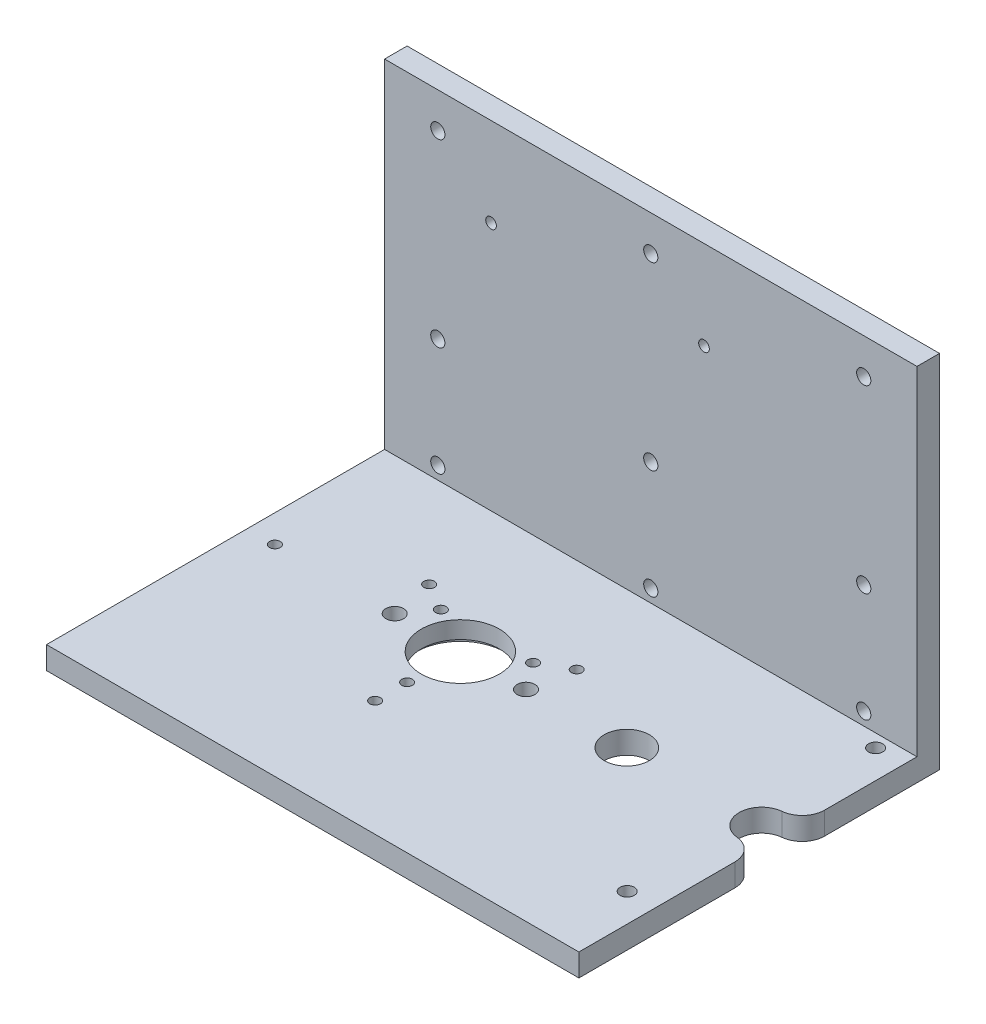
SolidWorks part; units mm, degrees
ref_plane "Alzado" through (0, 0, 0) normal (0, 0, 1) x (1, 0, 0)
ref_plane "Planta" through (0, 0, 0) normal (0, 1, 0) x (1, 0, 0)
ref_plane "Vista lateral" through (0, 0, 0) normal (1, 0, 0) x (0, 0, -1)
sketch "Croquis1" plane through (0, 0, 0) normal (0, 1, 0) x (1, 0, 0)
  line L1 (-75, 50.8) -> (75, 50.8)
  line L2 (-75, 50.8) -> (-75, -50.8)
  line L3 (-75, -50.8) -> (75, -50.8)
  line L4 (75, 50.8) -> (75, -50.8)
  line L5 (-75, 50.8) -> (75, -50.8) construction
  line L6 (-75, -50.8) -> (75, 50.8) construction
  point P0 (0, 0)
  dimension "D1" = 101.6
  dimension "D2" = 150
extrude "Saliente-Extruir1" add sketch "Croquis1" along normal mid plane 6.35
sketch "Croquis2" plane through (0, 3.175, 0) normal (0, 1, 0) x (1, 0, 0)
  line L0 (67, 50.8) -> (67, -50.8) construction
  line L1 (75, 50.8) -> (-75, 50.8) construction
  line L2 (-75, -50.8) -> (75, -50.8) construction
  line L3 (-75, 5.8) -> (75, 5.8) construction
  line L4 (-75, 50.8) -> (-75, -50.8) construction
  line L5 (75, -50.8) -> (75, 50.8) construction
  line L6 (-15, -95.8) -> (-15, 5.8) construction
  line L7 (-75, -50.8) -> (-75, -30.8) construction
  line L8 (-75, -30.8) -> (75, -30.8) construction
  line L9 (-15, 107.4) -> (218.4176, 107.4) construction
  line L10 (218.4176, 107.4) -> (218.4176, 30.4) construction
  line L11 (218.4176, 30.4) -> (-75, 30.4) construction
  line L12 (75, 30.8) -> (-75, 30.8) construction
  line L13 (0, 30.8) -> (0, 107.4) construction
  circle A0 centre (67, 40.8) radius 2
  circle A1 centre (67, -29.2) radius 2
  circle A2 centre (-15, 5.8) radius 11
  circle A3 centre (-67.25, 5.8) radius 1.5
  circle A4 centre (31.9, 5.8) radius 6.35
  circle A5 centre (69.9, 5.8) radius 6.35
  circle A6 centre (-15, 5.8) radius 101.6 construction
  dimension "D3" = 4
  dimension "D6" = 22
  dimension "D7" = 3
  dimension "D9" = 12.7
  dimension "D12" = 203.2
  dimension "D2" = 8
  dimension "D4" = 35
  dimension "D5" = 82
  dimension "D8" = 52.25
  dimension "D10" = 46.9
  dimension "D11" = 84.9
  dimension "D13" = 20
  dimension "D14" = 65
  dimension "D15" = 45
  dimension "D16" = 77
  dimension "D17" = 20
extrude "Cortar-Extruir1" cut sketch "Croquis2" against normal through all
fillet "Redondeo1" radius 6.35 2 edges at (75, 0, -9.5832) (75, 0, -2.0168)
sketch "Croquis3" plane through (0, 3.175, 0) normal (0, 1, 0) x (1, 0, 0)
  line L0 (-15, 5.8) -> (-15, -18.2) construction
  circle A0 centre (-15, -9.2) radius 1.5
  circle A1 centre (-15, -18.2) radius 1.5
  circle A2 centre (-15, 5.8) radius 20 construction
  circle A3 centre (-15, -18.2) radius 4 construction
  circle A4 centre (-27.9904, 13.3) radius 1.5
  circle A5 centre (-35.7846, 17.8) radius 1.5
  circle A6 centre (-2.0096, 13.3) radius 1.5
  circle A7 centre (5.7846, 17.8) radius 1.5
  point P19 (-15, 5.8)
  dimension "D1" = 3
  dimension "D2" = 3
  dimension "D5" = 40
  dimension "D6" = 8
  dimension "D3" = 15
  dimension "D4" = 24
  dimension "D7" = 3
extrude "Cortar-Extruir2" cut sketch "Croquis3" against normal through all
sketch "Croquis4" plane through (0, 0, 0) normal (0, 1, 0) x (1, 0, 0)
  circle A0 centre (-15, 5.8) radius 12.5
  dimension "D1" = 25
extrude "Cortar-Extruir3" cut sketch "Croquis4" along normal blind 1.5 from surface at -3.175 starting at face at (5.7846, -3.175, -16.3)
sketch "Croquis5" plane through (0, -3.175, 0) normal (0, -1, 0) x (1, 0, 0)
  line L0 (0, 0) -> (0, -50.8) construction
  line L1 (75, -50.8) -> (-75, -50.8) construction
  line L3 (-75, -44.45) -> (75, -44.45)
  line L4 (-75, -44.45) -> (-75, -50.8)
  line L5 (-75, -50.8) -> (75, -50.8)
  line L6 (75, -44.45) -> (75, -50.8)
  line L7 (-75, -44.45) -> (75, -50.8) construction
  line L8 (-75, -50.8) -> (75, -44.45) construction
  point P5 (0, -47.625)
  dimension "D1" = 6.35
extrude "Saliente-Extruir2" add sketch "Croquis5" against normal blind 101.6
sketch "Croquis6" plane through (0, 0, -50.8) normal (0, 0, -1) x (-1, 0, 0)
  line L0 (0, 98.425) -> (0, -3.175) construction
  line L1 (75, 98.425) -> (-75, 98.425) construction
  line L2 (-75, -3.175) -> (75, -3.175) construction
  line L3 (-75, 6.825) -> (75, 6.825) construction
  line L4 (-75, 98.425) -> (-75, -3.175) construction
  line L5 (75, 98.425) -> (75, -3.175) construction
  line L6 (0, 47.625) -> (-75, 47.625) construction
  line L7 (-75, 37.625) -> (0, 37.625) construction
  line L8 (-60, 6.825) -> (-60, 37.625) construction
  circle A0 centre (-60, 6.825) radius 2
  circle A1 centre (0, 6.825) radius 2
  circle A2 centre (60, 6.825) radius 2
  circle A3 centre (60, 88.425) radius 2
  circle A4 centre (0, 88.425) radius 2
  circle A5 centre (-60, 88.425) radius 2
  circle A6 centre (-60, 37.625) radius 2
  circle A7 centre (0, 37.625) radius 2
  circle A8 centre (60, 37.625) radius 2
  dimension "D2" = 4
  dimension "D1" = 10
  dimension "D3" = 15
  dimension "D4" = 10
extrude "Cortar-Extruir4" cut sketch "Croquis6" against normal through all
sketch "Croquis7" plane through (0, -3.175, 0) normal (0, -1, 0) x (1, 0, 0)
  line L0 (-15, -5.8) -> (-15, -60.8) construction
  line L1 (75, -50.8) -> (-75, -50.8) construction
  line L2 (-125, -50.8) -> (-125, -70.8) construction
  line L9 (-190, -50.8) -> (160, -50.8) construction
  line L10 (-190, -50.8) -> (-190, -70.8) construction
  line L11 (-190, -70.8) -> (160, -70.8) construction
  line L12 (160, -50.8) -> (160, -70.8) construction
  line L13 (-190, -50.8) -> (160, -70.8) construction
  line L14 (-190, -70.8) -> (160, -50.8) construction
  line L15 (-145, -50.8) -> (-145, -70.8) construction
  line L16 (-100, -50.8) -> (-100, -70.8) construction
  line L17 (-15, -107.4) -> (-193.2942, -107.4) construction
  line L18 (-190, -50.8) -> (-190, -30.8) construction
  line L19 (-190, -30.8) -> (-15, -30.8) construction
  line L20 (-15, -70.8) -> (-15, -90.8) construction
  line L21 (-15, -90.8) -> (-52.7811, -90.8) construction
  line L22 (-52.7811, -90.8) -> (-52.7811, -70.8) construction
  circle A0 centre (-15, -5.8) radius 101.6 construction
  circle A1 centre (-125, -82.5) radius 24.9 construction
  circle A2 centre (-165, -82.5) radius 24.9 construction
  dimension "D4" = 45
  dimension "D1" = 203.2
  dimension "D7" = 49.8
  dimension "D2" = 20
  dimension "D3" = 350
  dimension "D5" = 45
  dimension "D6" = 20
  dimension "D8" = 20
  dimension "D9" = 76.6
  dimension "D10" = 20
sketch "Croquis8" plane through (0, -3.175, 0) normal (0, -1, 0) x (1, 0, 0)
  line L0 (-15, -5.8) -> (-15, 6.7) construction
  line L1 (-15, -5.8) -> (3.5, -5.8) construction
  circle A0 centre (-15, -5.8) radius 12.5 construction
  circle A1 centre (3.5, -5.8) radius 2.5
  circle A2 centre (-33.5, -5.8) radius 2.5
  dimension "D2" = 5
  dimension "D1" = 18.5
extrude "Cortar-Extruir5" cut sketch "Croquis8" against normal through all
chamfer "Chaflán2" distance 2.5 angle 45 2 edges at (-33.5, -3.175, -3.3) (3.5, -3.175, -8.3)
sketch "Croquis9" plane through (0, 0, -50.8) normal (0, 0, -1) x (-1, 0, 0)
  line L0 (-75, 73.425) -> (15, 73.425) construction
  line L1 (-75, 98.425) -> (-75, -3.175) construction
  line L2 (15, 73.425) -> (15, 98.425) construction
  line L3 (75, 98.425) -> (-75, 98.425) construction
  circle A0 centre (-15, 73.425) radius 1.5
  circle A1 centre (45, 73.425) radius 1.5
  dimension "D3" = 3
  dimension "D1" = 90
  dimension "D2" = 25
  dimension "D4" = 30
extrude "Cortar-Extruir6" cut sketch "Croquis9" against normal through all
sketch "Croquis10" plane through (0, -3.175, 0) normal (0, -1, 0) x (1, 0, 0)
  line L0 (-75, -30.8) -> (75, -30.8) construction
  line L3 (-75, -50.8) -> (-75, 50.8) construction
  line L4 (75, -18.4383) -> (75, -50.8) construction
  line L5 (75, -50.8) -> (-75, -50.8) construction
  line L6 (-15, -107.4) -> (-15, -30.8) construction
  circle A0 centre (-15, -5.8) radius 101.6 construction
  dimension "D1" = 203.2
  dimension "D2" = 20
